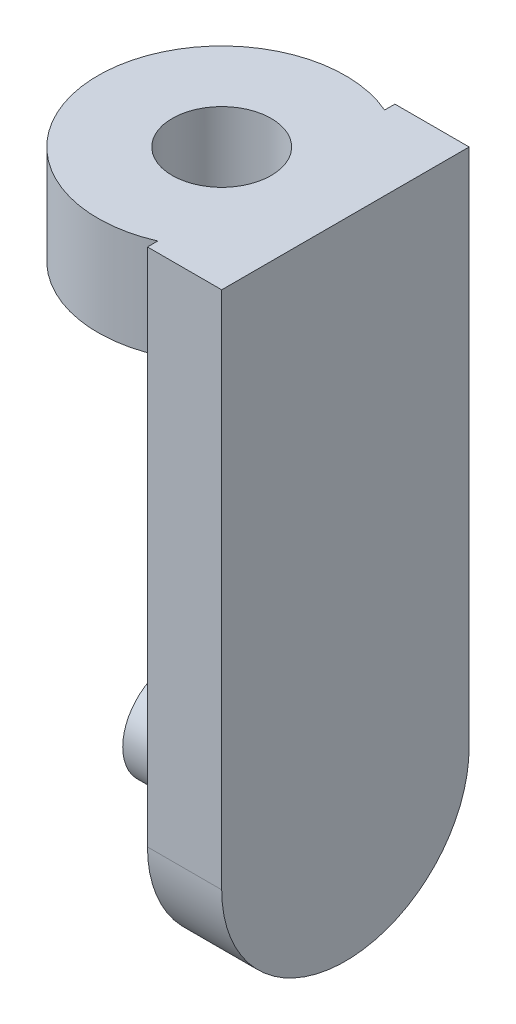
SolidWorks part; units mm, degrees
ref_plane "Front Plane" through (0, 0, 0) normal (0, 0, 1) x (1, 0, 0)
ref_plane "Top Plane" through (0, 0, 0) normal (0, 1, 0) x (1, 0, 0)
ref_plane "Right Plane" through (0, 0, 0) normal (1, 0, 0) x (0, 0, -1)
sketch "Sketch1" plane through (0, 0, 0) normal (0, 1, 0) x (1, 0, 0)
  circle A0 centre (0, 0) radius 1
  circle A1 centre (0, 0) radius 2.5
  dimension "D1" = 2
  dimension "D2" = 5
extrude "Boss-Extrude1" add sketch "Sketch1" along normal mid plane 2
ref_plane "Plane1" through (2.5, 0, 0) normal (1, 0, 0) x (0, 0, -1)
sketch "Sketch2" plane through (2.5, 0, 0) normal (1, 0, 0) x (0, 0, -1)
  line L1 (-2.5, 1) -> (2.5, 1)
  line L2 (-2.5, 1) -> (-2.5, -9.5)
  line L4 (2.5, 1) -> (2.5, -9.5)
  arc A0 (2.5, -9.5) -> (-2.5, -9.5) centre (0, -9.5) cw
  dimension "D3" = 2.5
  dimension "D1" = 5
  dimension "D2" = 10.5
extrude "Boss-Extrude2" add sketch "Sketch2" against normal blind 1.5
sketch "Sketch3" plane through (0, 1, 0) normal (0, 1, 0) x (1, 0, 0)
  circle A0 centre (0, 0) radius 2.5
  circle A1 centre (0, 0) radius 4
  dimension "D1" = 5
  dimension "D2" = 8
sketch "Sketch5" plane through (1, 0, 0) normal (-1, 0, 0) x (0, 0, 1)
  line L1 (-2.5, -9.5) -> (-2.5, 1) construction
  circle A0 centre (0, -9.5) radius 1
  point P2 (0, 0)
  point P6 (0, 0)
  dimension "D2" = 2
  dimension "D1" = 9.5
  dimension "D3" = 2.5
extrude "Boss-Extrude3" add sketch "Sketch5" along normal blind 2
